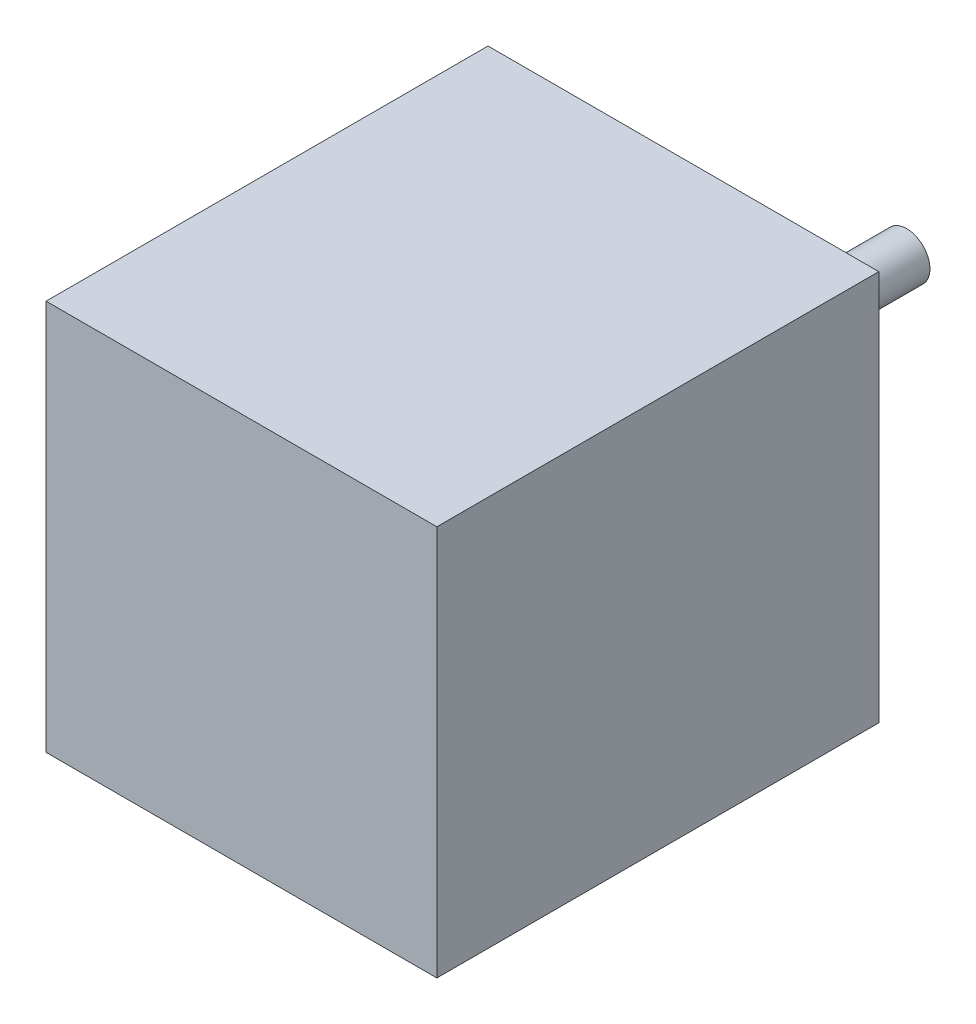
SolidWorks part; units mm, degrees
other "标注1"
sketch "草图7" plane through (-42, 0, -24) normal (-1, 0, 0) x (0, 0, 1)
ref_plane "前视基准面" through (0, 0, 0) normal (0, 0, 1) x (1, 0, 0)
ref_plane "上视基准面" through (0, 0, 0) normal (0, 1, 0) x (1, 0, 0)
ref_plane "右视基准面" through (0, 0, 0) normal (1, 0, 0) x (0, 0, -1)
sketch "草图1" plane through (0, 0, 0) normal (0, 0, 1) x (1, 0, 0)
  line L1 (0, 0) -> (-42, 0)
  line L2 (0, 0) -> (0, 42)
  line L3 (0, 42) -> (-42, 42)
  line L4 (-42, 0) -> (-42, 42)
  dimension "D1" = 42
  dimension "D2" = 42
extrude "凸台-拉伸1" add sketch "草图1" along normal blind 47.5
sketch "草图3" plane through (0, 0, 0) normal (0, 0, -1) x (-1, 0, 0)
  line L0 (0, 42) -> (42, 42) construction
  line L1 (0, 0) -> (0, 42) construction
  circle A0 centre (21, 21) radius 11
  dimension "D3" = 22
  dimension "D1" = 21
  dimension "D2" = 21
extrude "凸台-拉伸2" add sketch "草图3" along normal blind 2
sketch "草图4" plane through (0, 0, -2) normal (0, 0, -1) x (-1, 0, 0)
  circle A0 centre (21, 21) radius 2.5
  dimension "D1" = 5
extrude "凸台-拉伸3" add sketch "草图4" along normal blind 22
sketch "草图5" plane through (0, 0, 0) normal (0, 0, -1) x (-1, 0, 0)
  line L0 (0, 0) -> (5.5, 0) construction
  line L1 (42, 0) -> (0, 0) construction
  line L2 (5.5, 0) -> (5.5, 5.5) construction
  line L3 (5.5, 5.5) -> (36.5, 5.5) construction
  line L4 (36.5, 5.5) -> (36.5, 36.5) construction
  line L5 (36.5, 36.5) -> (5.5, 36.5) construction
  circle A0 centre (5.5, 5.5) radius 1.5
  circle A1 centre (36.5, 5.5) radius 1.5
  circle A2 centre (36.5, 36.5) radius 1.5
  circle A3 centre (5.5, 36.5) radius 1.5
  dimension "D6" = 3
  dimension "D7" = 3
  dimension "D8" = 3
  dimension "D9" = 3
  dimension "D1" = 5.5
  dimension "D2" = 5.5
  dimension "D3" = 31
  dimension "D4" = 31
  dimension "D5" = 31
extrude "切除-拉伸1" cut sketch "草图5" against normal blind 8
